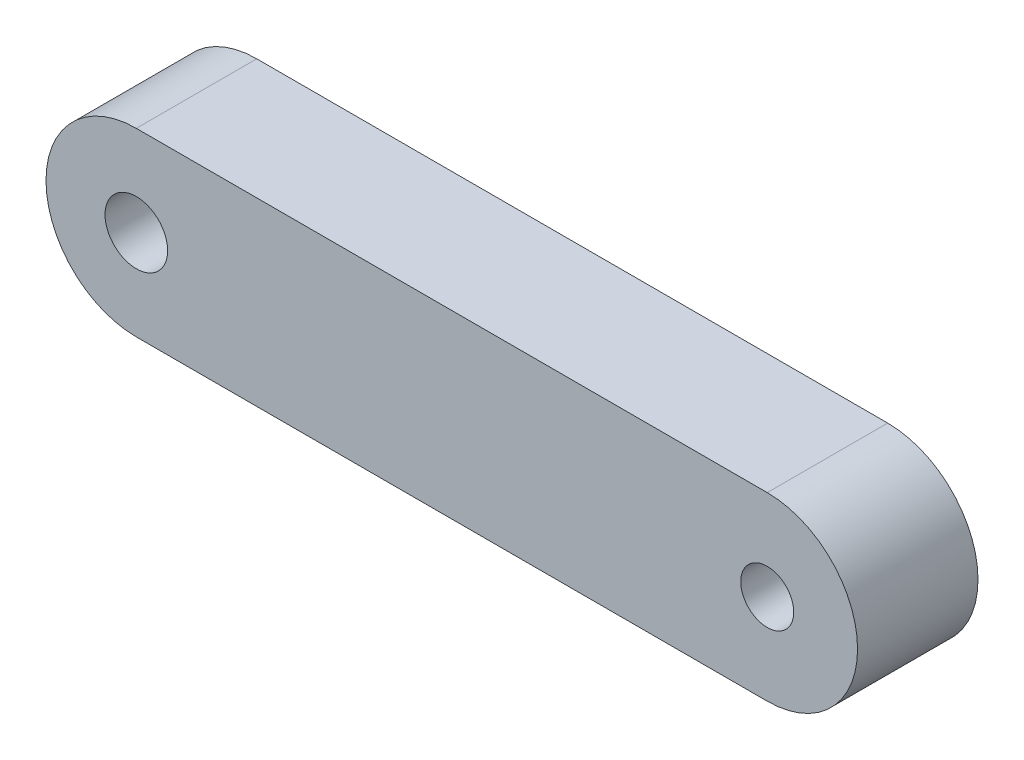
SolidWorks part; units mm, degrees
ref_plane "Front Plane" through (0, 0, 0) normal (0, 0, 1) x (1, 0, 0)
ref_plane "Top Plane" through (0, 0, 0) normal (0, 1, 0) x (1, 0, 0)
ref_plane "Right Plane" through (0, 0, 0) normal (1, 0, 0) x (0, 0, -1)
sketch "Sketch1" plane through (0, 0, 0) normal (0, 0, 1) x (1, 0, 0)
  line L0 (-16.6324, 0) -> (16.6324, 0) construction
  line L1 (-16.6324, 4.7625) -> (16.6324, 4.7625)
  line L2 (-16.6324, -4.7625) -> (16.6324, -4.7625)
  arc A0 (-16.6324, 4.7625) -> (-16.6324, -4.7625) centre (-16.6324, 0) ccw
  arc A1 (16.6324, -4.7625) -> (16.6324, 4.7625) centre (16.6324, 0) ccw
  circle A2 centre (16.6324, 0) radius 1.3969
  circle A3 centre (-16.6324, 0) radius 1.65
  point P2 (0, 0)
  dimension "D1" = 42.7897
  dimension "D2" = 2.7938
  dimension "D4" = 3.3
  dimension "D3" = 9.525
extrude "Boss-Extrude1" add sketch "Sketch1" along normal blind 6.35
sketch "Sketch2" plane through (0, 0, 0) normal (0, 0, -1) x (-1, 0, 0)
  circle A0 centre (16.6324, 0) radius 3.1
  dimension "D1" = 6.2
extrude "Cut-Extrude1" cut sketch "Sketch2" against normal blind 3.75
